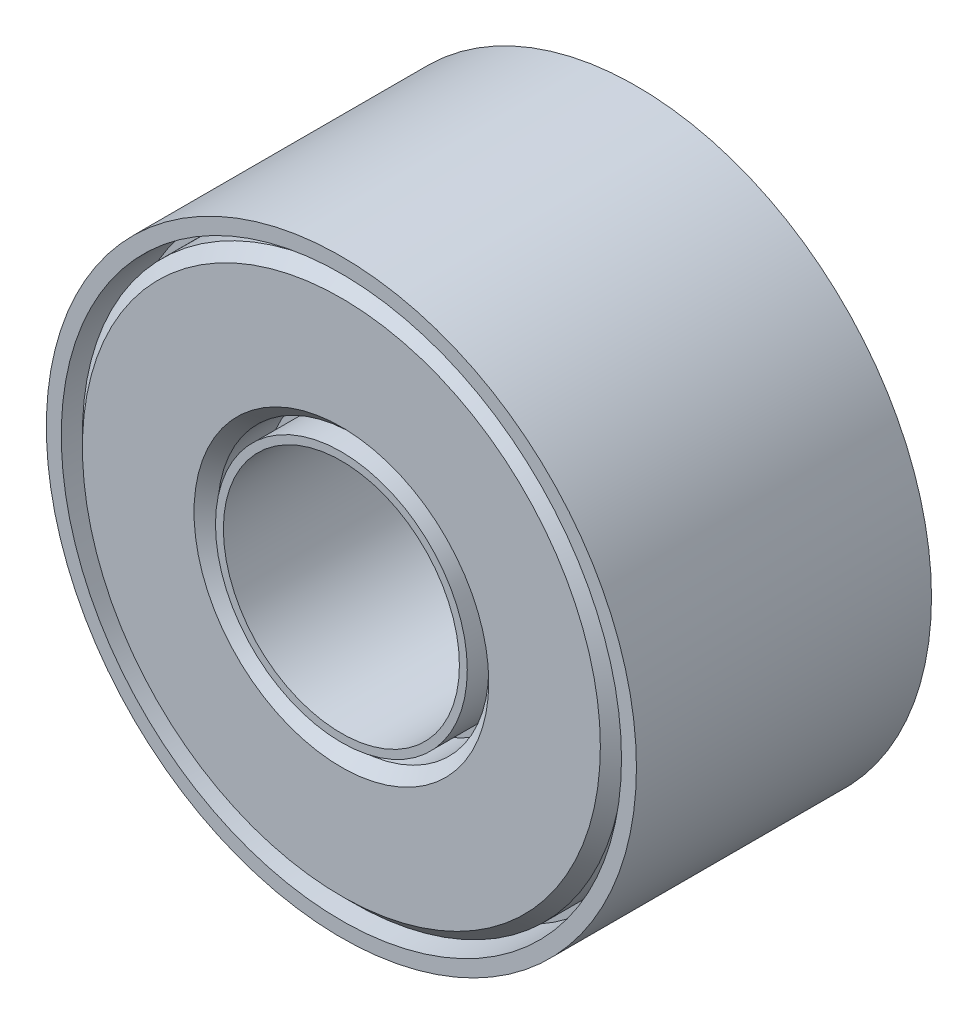
SolidWorks part; units mm, degrees
material "AISI 304"
ref_plane "Front Plane" through (0, 0, 0) normal (0, 0, 1) x (1, 0, 0)
ref_plane "Top Plane" through (0, 0, 0) normal (0, 1, 0) x (1, 0, 0)
ref_plane "Right Plane" through (0, 0, 0) normal (1, 0, 0) x (0, 0, -1)
other "Configuration Table"
sketch "Sketch1" plane through (0, 0, 0) normal (0, 0, 1) x (1, 0, 0)
  circle A0 centre (0, 0) radius 2.5
  circle A1 centre (0, 0) radius 1
  dimension "D1" = 5
  dimension "D2" = 2
extrude "Boss-Extrude1" add sketch "Sketch1" along normal blind 2.5
sketch "Sketch2" plane through (0, 0, 2.5) normal (0, 0, 1) x (1, 0, 0)
  circle A0 centre (0, 0) radius 1.0667
  circle A1 centre (0, 0) radius 1.1486
  circle A2 centre (0, 0) radius 2.3735
  circle A3 centre (0, 0) radius 2.2943
extrude "Cut-Extrude1" cut sketch "Sketch2" against normal blind 0.5 contours A1 A0 | A2 A3
chamfer "Chamfer1" distance 0.1 angle 45 2 edges at (2.2943, 0, 2.5) (1.1486, 0, 2.5)
ref_plane "Plane1" through (0, 0, 1.25) normal (0, 0, -1) x (-1, 0, 0)
mirror "Mirror3" about plane through (0, 0, 1.25) normal (0, 0, -1) of "Cut-Extrude1"
chamfer "Chamfer2" distance 0.1 angle 45 2 edges at (1.1486, 0, 0) (2.2943, 0, 0)
